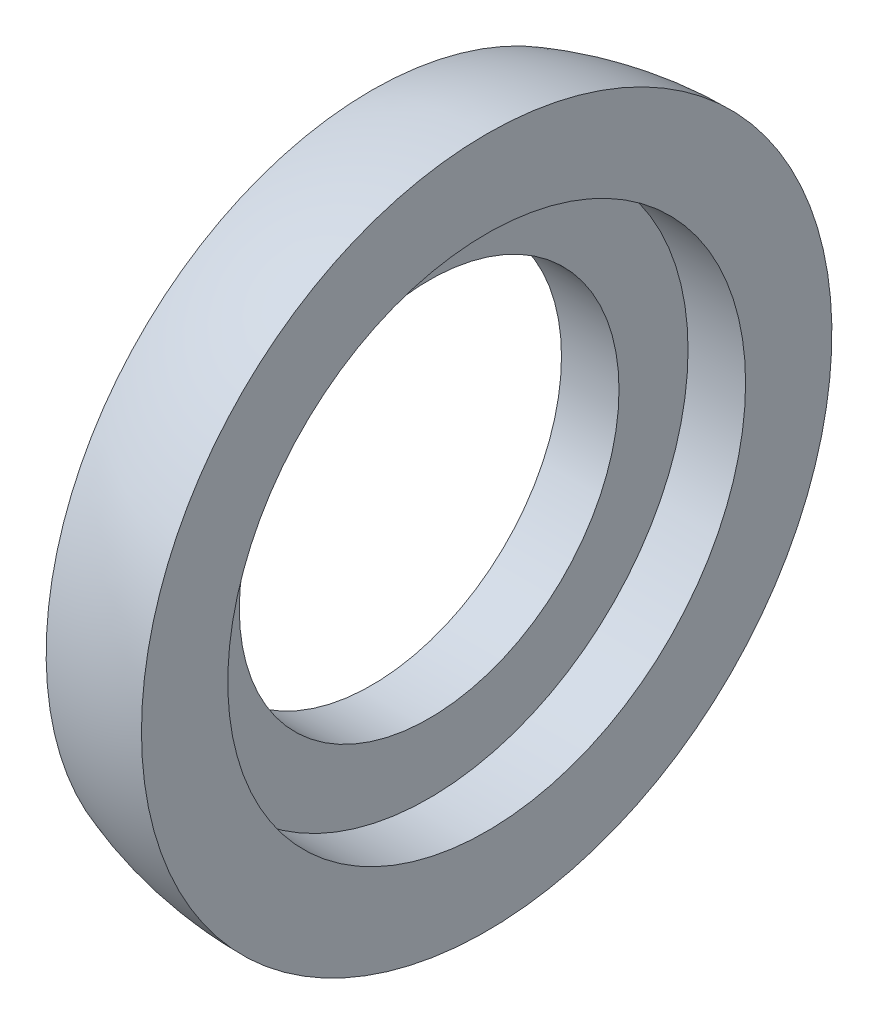
SolidWorks part; units mm, degrees
ref_plane "前视基准面" through (0, 0, 0) normal (0, 0, 1) x (1, 0, 0)
ref_plane "上视基准面" through (0, 0, 0) normal (0, 1, 0) x (1, 0, 0)
ref_plane "右视基准面" through (0, 0, 0) normal (1, 0, 0) x (0, 0, -1)
other "Configuration Table"
sketch "草图1" plane through (0, 0, 0) normal (1, 0, 0) x (0, 0, -1)
  line L0 (0, 12) -> (0, -12)
  arc A0 (0, 12) -> (0, -12) centre (0, 0) ccw
  dimension "D1" = 12
revolve "旋转1" add sketch "草图1" angle 180 about L0
sketch "草图5" plane through (0, 0, 0) normal (0, 0, 1) x (1, 0, 0)
  line L0 (0, -12) -> (0, 12) construction
  line L1 (-12, 15.7752) -> (-4, 15.7752)
  line L2 (-12, 15.7752) -> (-12, -14.2248)
  line L3 (-12, -14.2248) -> (-4, -14.2248)
  line L4 (-4, 15.7752) -> (-4, -14.2248)
  dimension "D1" = 30
  dimension "D2" = 4
  dimension "D3" = 8
extrude "切除-拉伸3" cut sketch "草图5" against normal through all and the other way through all
sketch "草图11" plane through (0, 0, 0) normal (1, 0, 0) x (0, 0, -1)
  circle A0 centre (0, 0) radius 6.6
  dimension "D1" = 13.2
extrude "切除-拉伸7" cut sketch "草图11" against normal through all
sketch "草图12" plane through (0, 0, 0) normal (1, 0, 0) x (0, 0, -1)
  circle A0 centre (0, 0) radius 9
  dimension "D1" = 18
extrude "切除-拉伸8" cut sketch "草图12" against normal blind 2
